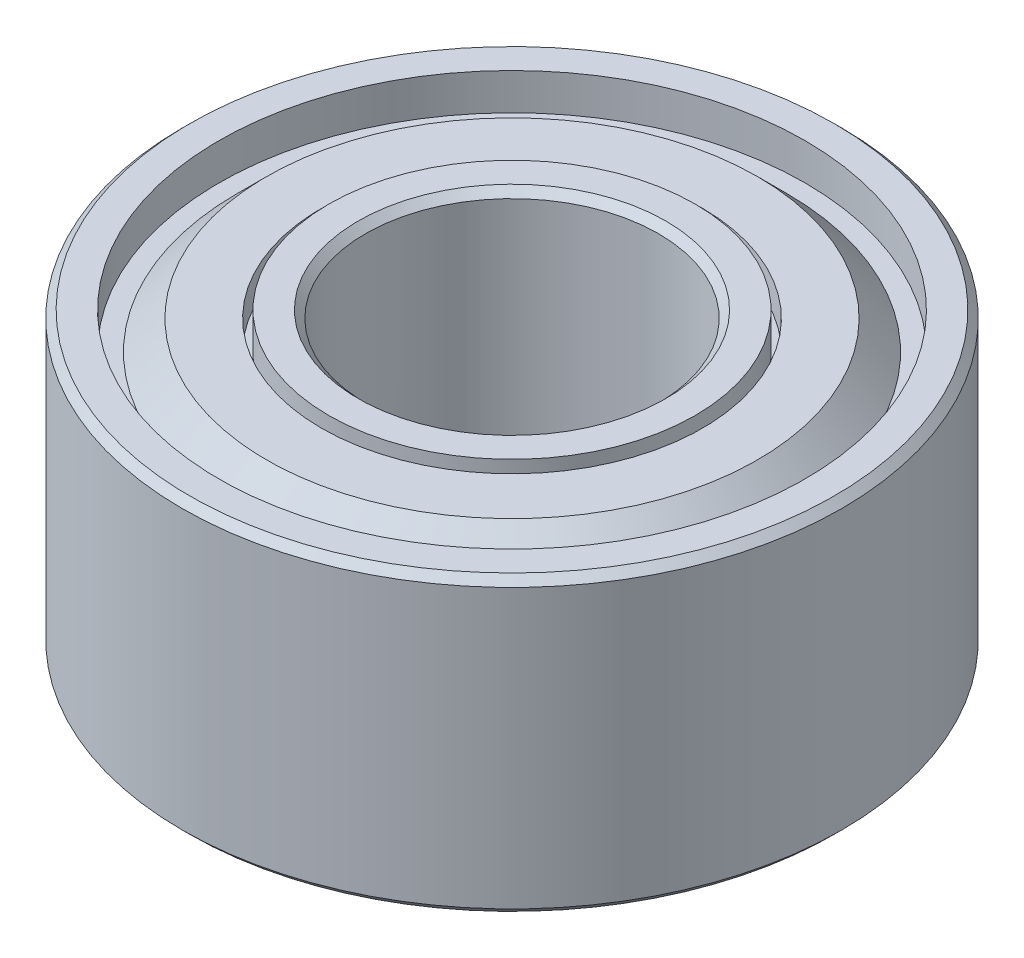
SolidWorks part; units mm, degrees
material "Chrome Stainless Steel"
ref_plane "Front Plane" through (0, 0, 0) normal (0, 0, 1) x (1, 0, 0)
ref_plane "Top Plane" through (0, 0, 0) normal (0, 1, 0) x (1, 0, 0)
ref_plane "Right Plane" through (0, 0, 0) normal (1, 0, 0) x (0, 0, -1)
sketch "Sketch1" plane through (0, 0, 0) normal (1, 0, 0) x (0, 0, -1)
  line L0 (-2, 2) -> (-2, -2)
  line L6 (-4.5, -2) -> (-4.5, 2)
  line L7 (-4.5, 2) -> (-4, 2)
  line L8 (-4, 2) -> (-4, 1.5)
  line L10 (-2.5, 1.5) -> (-2.5, 2)
  line L11 (-2.5, 2) -> (-2, 2)
  line L12 (0, -2) -> (0, 2) construction
  line L13 (0, 2) -> (-2, 2) construction
  line L14 (0, -2) -> (-2, -2) construction
  line L15 (-4, 1.5) -> (-3.75, 1.5)
  line L16 (-3.75, 1.5) -> (-3.35, 1.9)
  line L17 (-3.35, 1.9) -> (-2.6, 1.9)
  line L18 (-2.6, 1.9) -> (-2.6, 1.5)
  line L19 (-2.6, 1.5) -> (-2.5, 1.5)
  line L20 (0, 0) -> (-4.5, 0) construction
  line L21 (-2.6, -1.5) -> (-2.5, -1.5)
  line L22 (-2.6, -1.9) -> (-2.6, -1.5)
  line L23 (-3.35, -1.9) -> (-2.6, -1.9)
  line L24 (-3.75, -1.5) -> (-3.35, -1.9)
  line L25 (-4, -1.5) -> (-3.75, -1.5)
  line L26 (-2.5, -2) -> (-2, -2)
  line L27 (-2.5, -1.5) -> (-2.5, -2)
  line L28 (-4, -2) -> (-4, -1.5)
  line L29 (-4.5, -2) -> (-4, -2)
  point P2 (0, 0)
  point P27 (-2, 0)
  dimension "D1" = 4.5
  dimension "D2" = 2
  dimension "D3" = 2
  dimension "D4" = 0.5
  dimension "D5" = 0.5
  dimension "D6" = 0.25
  dimension "D7" = 45
  dimension "D8" = 0.1
  dimension "D9" = 0.1
revolve "Revolve1" add sketch "Sketch1" angle 360 about L12
chamfer "Chamfer1" distance 0.1 angle 45 4 edges at (0, 2, -2) (0, -2, -4.5) (0, 2, -4.5) (0, -2, -2)
